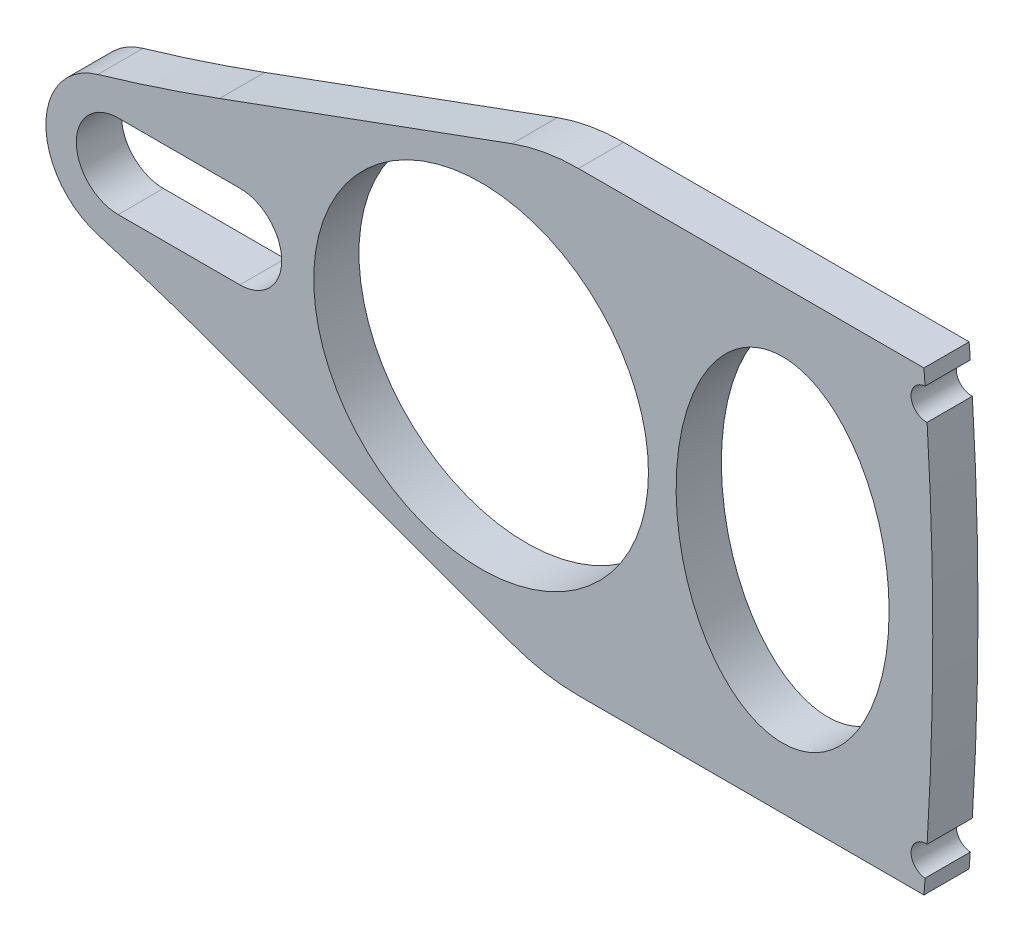
SolidWorks part; units mm, degrees
ref_plane "Front Plane" through (0, 0, 0) normal (0, 0, 1) x (1, 0, 0)
ref_plane "Top Plane" through (0, 0, 0) normal (0, 1, 0) x (1, 0, 0)
ref_plane "Right Plane" through (0, 0, 0) normal (1, 0, 0) x (0, 0, -1)
sketch "Sketch1" plane through (0, 0, 0) normal (0, 0, 1) x (1, 0, 0)
  line L0 (-7.933, 20.1848) -> (-30.8487, 20.1848)
  line L1 (-35.2546, 19.4037) -> (-54.6534, 12.3023)
  line L2 (-54.6534, -2.2085) -> (-35.2546, -9.3098)
  line L3 (-30.8487, -10.0909) -> (-7.933, -10.0909)
  line L4 (-53.3047, 2.2716) -> (-61.3782, 2.2716)
  line L5 (-61.3782, 7.8222) -> (-53.3047, 7.8222)
  line L6 (-66.1719, 5.0469) -> (-7.3465, 5.0469) construction
  arc A0 (-8.7664, -7.8807) -> (-7.8575, -9.0846) centre (-7.7768, -8.0786) ccw
  arc A1 (-7.7221, -7.0709) -> (-8.7664, -7.8807) centre (-7.7768, -8.0786) ccw
  arc A2 (-7.7221, -7.0709) -> (-7.7221, 17.1647) centre (-202.995, 5.0469) ccw
  arc A3 (-8.7664, 18.3703) -> (-7.7221, 17.1647) centre (-7.7768, 18.1724) ccw
  arc A4 (-7.8575, 19.1784) -> (-8.7664, 18.3703) centre (-7.7768, 18.1724) ccw
  arc A5 (-7.8575, 19.1784) -> (-7.933, 20.1848) centre (-202.995, 5.0469) ccw
  arc A6 (-30.8487, 20.1848) -> (-35.2546, 19.4037) centre (-30.8487, 7.368) ccw
  arc A7 (-62.7243, 9.6477) -> (-54.6534, 12.3023) centre (-98.7124, 132.6585) ccw
  arc A8 (-62.7243, 9.6477) -> (-62.7243, 0.4461) centre (-61.3782, 5.0469) ccw
  arc A9 (-54.6534, -2.2085) -> (-62.7243, 0.4461) centre (-98.7124, -122.5647) ccw
  arc A10 (-35.2546, -9.3098) -> (-30.8487, -10.0909) centre (-30.8487, 2.7258) ccw
  arc A11 (-7.933, -10.0909) -> (-7.8575, -9.0846) centre (-202.995, 5.0469) ccw
  circle A12 centre (-37.3047, 5.0469) radius 11.1011
  arc A13 (-61.3782, 7.8222) -> (-61.3782, 2.2716) centre (-61.3782, 5.0469) ccw
  arc A14 (-53.3047, 2.2716) -> (-53.3047, 7.8222) centre (-53.3047, 5.0469) ccw
  ellipse E0 centre (-17.3047, 5.0469) end of major axis (-17.3047, -6.0542) minor radius 7.0643
  point P42 (-37.3047, 5.0469)
  point P45 (-17.3047, 5.0469)
  point P46 (0, 0)
  point P47 (0, 0)
  point P48 (-37.3047, 5.0469)
  point P49 (0, 0)
  point P50 (0, 0)
  point P51 (0, 0)
  dimension "D1" = 16
  dimension "D2" = 20
extrude "Boss-Extrude1" add sketch "Sketch1" along normal blind 3
